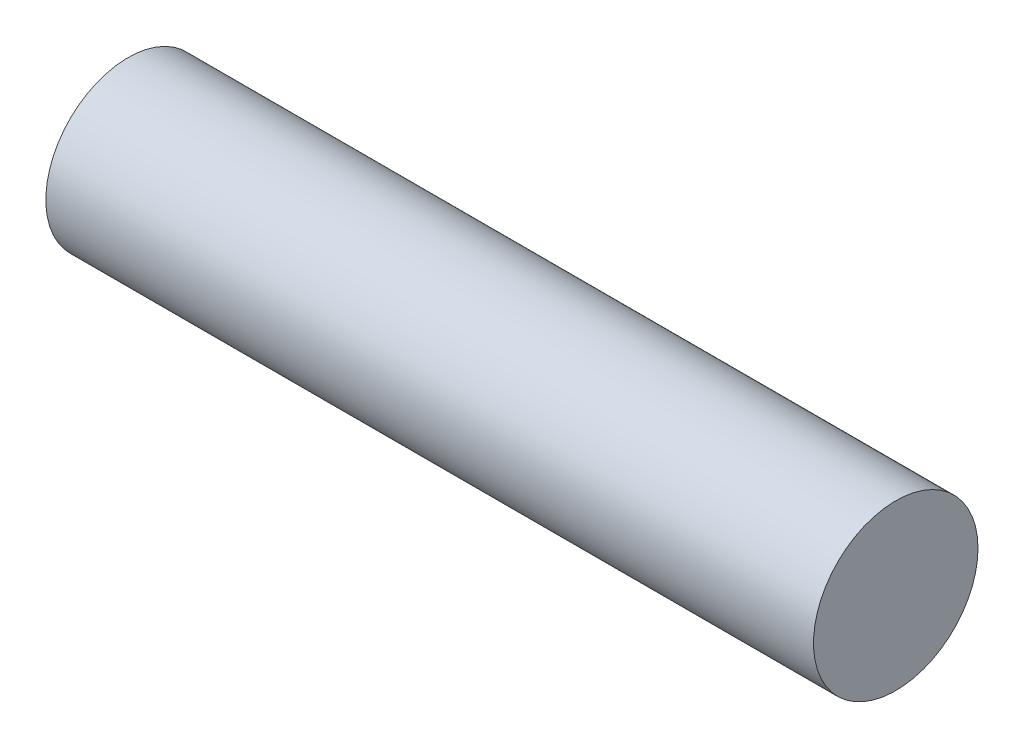
SolidWorks part; units mm, degrees
ref_plane "Front Plane" through (0, 0, 0) normal (0, 0, 1) x (1, 0, 0)
ref_plane "Top Plane" through (0, 0, 0) normal (0, 1, 0) x (1, 0, 0)
ref_plane "Right Plane" through (0, 0, 0) normal (1, 0, 0) x (0, 0, -1)
sketch "Sketch1" plane through (0, 0, 0) normal (1, 0, 0) x (0, 0, -1)
  circle A0 centre (0, 0) radius 1.5
  dimension "D1" = 3
extrude "Boss-Extrude1" add sketch "Sketch1" along normal blind 14
